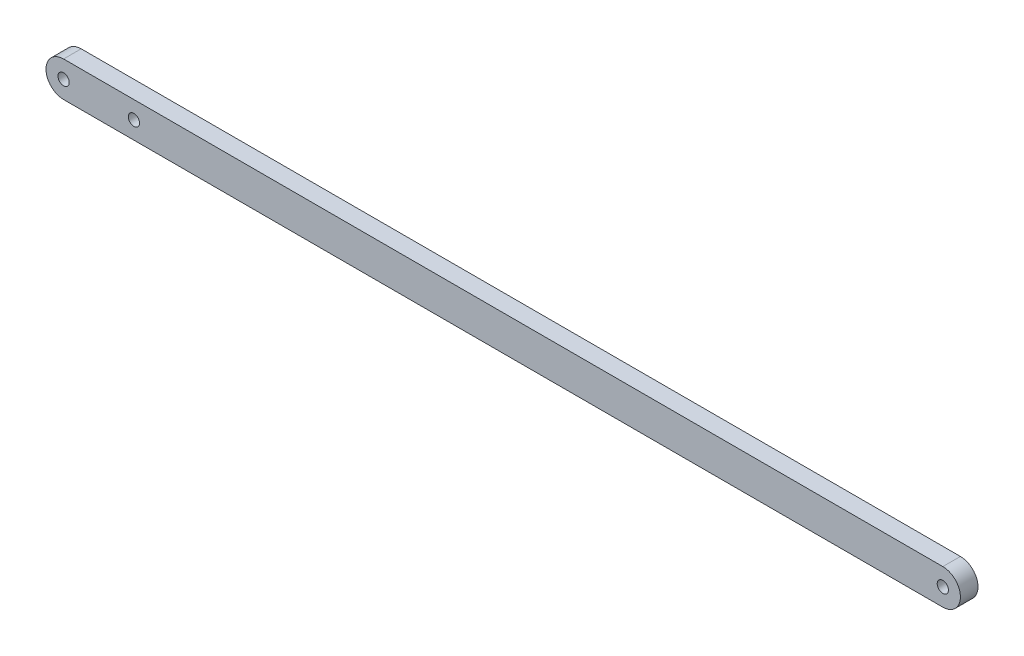
SolidWorks part; units mm, degrees
ref_plane "Front Plane" through (0, 0, 0) normal (0, 0, 1) x (1, 0, 0)
ref_plane "Top Plane" through (0, 0, 0) normal (0, 1, 0) x (1, 0, 0)
ref_plane "Right Plane" through (0, 0, 0) normal (1, 0, 0) x (0, 0, -1)
sketch "Sketch1" plane through (0, 0, 0) normal (0, 0, 1) x (1, 0, 0)
  line L0 (0, 0) -> (317.5, 0) construction
  line L1 (0, 6.35) -> (317.5, 6.35)
  line L2 (0, -6.35) -> (317.5, -6.35)
  arc A0 (0, 6.35) -> (0, -6.35) centre (0, 0) ccw
  arc A1 (317.5, -6.35) -> (317.5, 6.35) centre (317.5, 0) ccw
  circle A2 centre (0, 0) radius 2.032
  circle A3 centre (317.5, 0) radius 2.032
  circle A4 centre (25.4, 0) radius 2.032
  point P3 (158.75, 0)
  dimension "D3" = 292.1
  dimension "D4" = 4.064
  dimension "D1" = 317.5
  dimension "D2" = 12.7
extrude "Boss-Extrude1" add sketch "Sketch1" along normal mid plane 6.35
